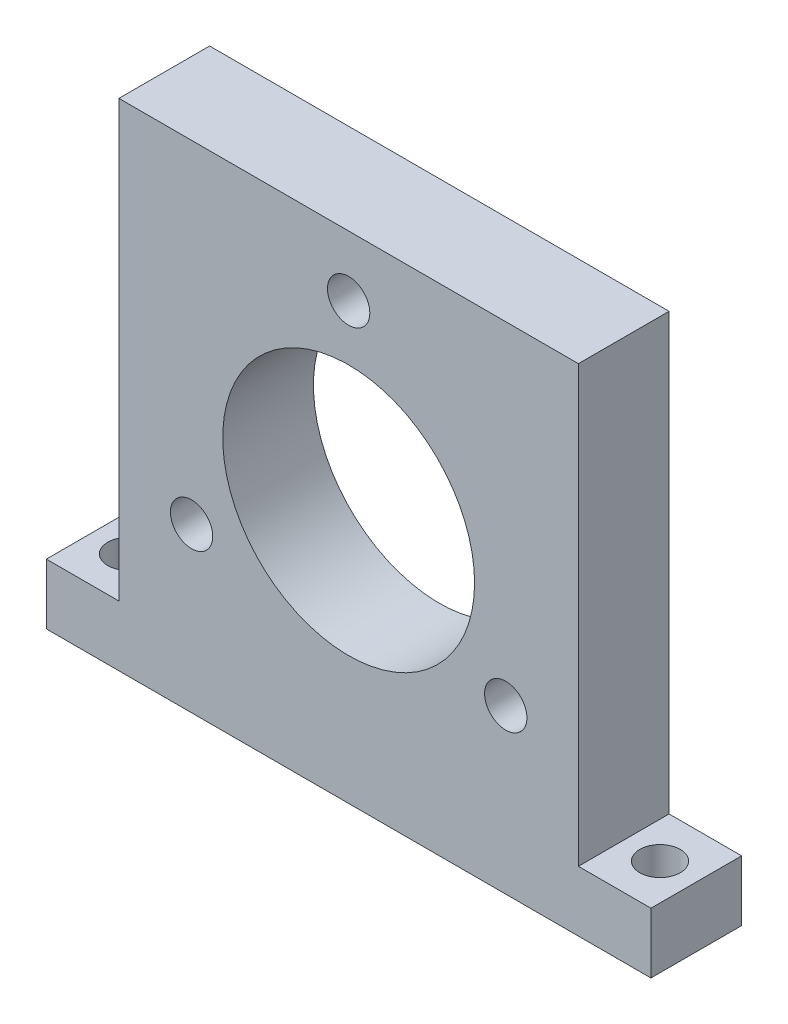
SolidWorks part; units mm, degrees
material "6061-T6 (SS)"
ref_plane "Frontal Plane" through (0, 0, 0) normal (0, 0, 1) x (1, 0, 0)
ref_plane "Horizontal Plane" through (0, 0, 0) normal (0, 1, 0) x (1, 0, 0)
ref_plane "Profile Plane" through (0, 0, 0) normal (1, 0, 0) x (0, 0, -1)
sketch "Sketch2" plane through (0, 0, 0) normal (0, 0, 1) x (1, 0, 0)
  line L0 (-25, 0) -> (25, 0)
  line L1 (25, 0) -> (25, 5)
  line L2 (25, 5) -> (19, 5)
  line L3 (19, 5) -> (19, 41)
  line L4 (19, 41) -> (-19, 41)
  line L5 (-19, 41) -> (-19, 5)
  line L6 (-19, 5) -> (-25, 5)
  line L7 (-25, 5) -> (-25, 0)
  circle A0 centre (0, 21) radius 10.414
  point P4 (0, 0)
  point P11 (0, 41)
  dimension "D2" = 20.828
  dimension "D1" = 38
  dimension "D3" = 5
  dimension "D5" = 21
  dimension "D4" = 6
  dimension "D6" = 20
extrude "Boss-Extrude1" add sketch "Sketch2" against normal blind 7.5
ref_plane "Plane1" through (0, 0, -7.5) normal (0, 0, -1) x (-1, 0, 0)
sketch "Sketch5" plane through (0, 0, 0) normal (0, 0, 1) x (1, 0, 0)
  line L0 (0, 36) -> (0, 21) construction
  circle A0 centre (0, 21) radius 15 construction
  circle A2 centre (0, 36) radius 1.75
  circle A5 centre (0, 21) radius 10.414 construction
  dimension "D1" = 30
  dimension "D4" = 3.5
extrude "Cut-Extrude3" cut sketch "Sketch5" against normal through all
pattern_circular "CirPattern1" count 3 over 360 about axis through (0, 21, 0) along (0, 0, 1) of "Cut-Extrude3"
sketch "Sketch6" plane through (0, 5, 0) normal (0, 1, 0) x (1, 0, 0)
  line L0 (-25, 7.5) -> (-25, 0) construction
  line L2 (25, 7.5) -> (25, 0) construction
  circle A0 centre (22, 3.75) radius 1.675
  circle A1 centre (-22, 3.75) radius 1.675
  point P6 (-25, 3.75)
  dimension "D1" = 3.35
  dimension "D2" = 3
  dimension "D3" = 3
extrude "Cut-Extrude4" cut sketch "Sketch6" against normal through all
equation "\"BaseL\"= 6ft"
equation "\"BaseW\"= 5.5in"
equation "\"BaseThickness\"= 1in"
equation "\"RailGap\"= 4cm"
equation "\"SlidePlateL\"= 8cm"
equation "\"SlidePlateW\"= 11cm"
equation "\"SlidePlateThickness\"= 5mm"
equation "\"SlidePlateClearance\"= 1cm"
equation "\"BoxThickness\"= .5cm"
equation "\"BoxX\"= \"RailGap\" + 30mm"
equation "\"BoxH\"= 2cm + \"SlidePlateClearance\" + \"SlidePlateThickness\" + 3cm"
equation "\"PulleyRadius\"= 15.1mm"
equation "\"PulleyH\"= 30mm + 21.4056mm - 2.5mm"
equation "\"PulleyShaftDiameter\"= .3125in"
equation "\"PulleyShaftL\"= 4in"
equation "\"PulleyShaft2L\"= 3in"
equation "\"MotorL\"= 4.43in"
equation "\"MotorRadius\"= 1.291in"
equation "\"MotorShaftRadius\"= .15625in"
equation "\"MotorShaftL\"= 1.75in"
equation "\"HeadstoneThickness\"= 7.5mm"
equation "\"BeltL\"= 1500mm + \"80\""
equation "\"BeltThickness\"= 2.5mm"
equation "\"BeltW\"= .375in"
equation "\"BeltLockH\"= \"PulleyH\" + 19.4056mm - (\"SlidePlateThickness\" + \"SlidePlateClearance\" + 15mm + 5mm)"
equation "\"EncoderL\"= 33mm"
equation "\"EncoderRadius\"= 19mm"
equation "\"EncoderShaftRadius\"= 3mm"
equation "\"EncoderShaftL\"= 15mm"
equation "\"PendulumShaftL\"= \"100mm\" "
equation "\"PendulumShaftRadius\"= 3mm"
equation "\"RodL\"= 39in"
equation "\"RodRadius\"= 3mm"
equation "\"D1@Sketch2\"=\"EncoderRadius\"*2"
equation "\"PillowBlockCenterH\"= \"EncoderRadius\" + 2mm"
